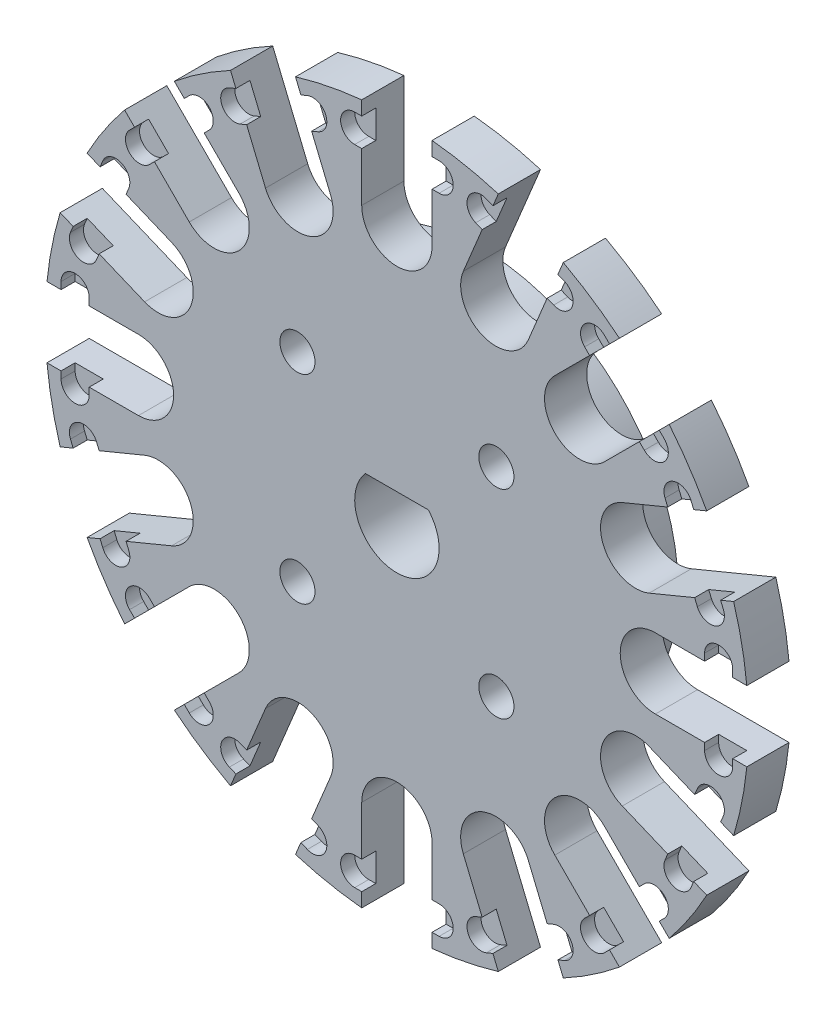
SolidWorks part; units mm, degrees
ref_plane "Plan de face" through (0, 0, 0) normal (0, 0, 1) x (1, 0, 0)
ref_plane "Plan de dessus" through (0, 0, 0) normal (0, 1, 0) x (1, 0, 0)
ref_plane "Plan de droite" through (0, 0, 0) normal (1, 0, 0) x (0, 0, -1)
sketch "Esquisse1" plane through (0, 0, 0) normal (0, 0, 1) x (1, 0, 0)
  circle A0 centre (0, 0) radius 25
  dimension "D1" = 50
extrude "Extrusion1" add sketch "Esquisse1" along normal blind 3
sketch "Esquisse2" plane through (0, 0, 3) normal (0, 0, 1) x (1, 0, 0)
  line L0 (-2.2361, 2) -> (2.2361, 2)
  line L1 (0, 35.6055) -> (0, -30.9749) construction
  line L2 (-2.5, 24.8747) -> (-2.5, 18.3747)
  line L3 (2.5, 24.8747) -> (2.5, 18.3747)
  line L4 (7.2094, 23.9379) -> (4.722, 17.9327)
  line L5 (11.8288, 22.0245) -> (9.3414, 16.0193)
  line L6 (15.8213, 19.3568) -> (11.2251, 14.7606)
  line L7 (19.3568, 15.8213) -> (14.7606, 11.2251)
  line L8 (22.0245, 11.8288) -> (16.0193, 9.3414)
  line L9 (23.9379, 7.2094) -> (17.9327, 4.722)
  line L10 (24.8747, 2.5) -> (18.3747, 2.5)
  line L11 (24.8747, -2.5) -> (18.3747, -2.5)
  line L12 (23.9379, -7.2094) -> (17.9327, -4.722)
  line L13 (22.0245, -11.8288) -> (16.0193, -9.3414)
  line L14 (19.3568, -15.8213) -> (14.7606, -11.2251)
  line L15 (15.8213, -19.3568) -> (11.2251, -14.7606)
  line L16 (11.8288, -22.0245) -> (9.3414, -16.0193)
  line L17 (7.2094, -23.9379) -> (4.722, -17.9327)
  line L18 (2.5, -24.8747) -> (2.5, -18.3747)
  line L19 (-2.5, -24.8747) -> (-2.5, -18.3747)
  line L20 (-7.2094, -23.9379) -> (-4.722, -17.9327)
  line L21 (-11.8288, -22.0245) -> (-9.3414, -16.0193)
  line L22 (-15.8213, -19.3568) -> (-11.2251, -14.7606)
  line L23 (-19.3568, -15.8213) -> (-14.7606, -11.2251)
  line L24 (-22.0245, -11.8288) -> (-16.0193, -9.3414)
  line L25 (-23.9379, -7.2094) -> (-17.9327, -4.722)
  line L26 (-24.8747, -2.5) -> (-18.3747, -2.5)
  line L27 (-24.8747, 2.5) -> (-18.3747, 2.5)
  line L28 (-23.9379, 7.2094) -> (-17.9327, 4.722)
  line L29 (-22.0245, 11.8288) -> (-16.0193, 9.3414)
  line L30 (-19.3568, 15.8213) -> (-14.7606, 11.2251)
  line L31 (-15.8213, 19.3568) -> (-11.2251, 14.7606)
  line L32 (-11.8288, 22.0245) -> (-9.3414, 16.0193)
  line L33 (-7.2094, 23.9379) -> (-4.722, 17.9327)
  arc A0 (-2.2361, 2) -> (2.2361, 2) centre (0, 0) ccw
  circle A1 centre (0, 0) radius 25 construction
  arc A2 (2.5, 18.3747) -> (-2.5, 18.3747) centre (0, 18.3747) cw
  arc A3 (11.8288, 22.0245) -> (7.2094, 23.9379) centre (0, 0) ccw
  arc A4 (9.3414, 16.0193) -> (4.722, 17.9327) centre (7.0317, 16.976) cw
  arc A5 (19.3568, 15.8213) -> (15.8213, 19.3568) centre (0, 0) ccw
  arc A6 (14.7606, 11.2251) -> (11.2251, 14.7606) centre (12.9929, 12.9929) cw
  arc A7 (23.9379, 7.2094) -> (22.0245, 11.8288) centre (0, 0) ccw
  arc A8 (17.9327, 4.722) -> (16.0193, 9.3414) centre (16.976, 7.0317) cw
  arc A9 (24.8747, -2.5) -> (24.8747, 2.5) centre (0, 0) ccw
  arc A10 (18.3747, -2.5) -> (18.3747, 2.5) centre (18.3747, 0) cw
  arc A11 (22.0245, -11.8288) -> (23.9379, -7.2094) centre (0, 0) ccw
  arc A12 (16.0193, -9.3414) -> (17.9327, -4.722) centre (16.976, -7.0317) cw
  arc A13 (15.8213, -19.3568) -> (19.3568, -15.8213) centre (0, 0) ccw
  arc A14 (11.2251, -14.7606) -> (14.7606, -11.2251) centre (12.9929, -12.9929) cw
  arc A15 (7.2094, -23.9379) -> (11.8288, -22.0245) centre (0, 0) ccw
  arc A16 (4.722, -17.9327) -> (9.3414, -16.0193) centre (7.0317, -16.976) cw
  arc A17 (-2.5, -24.8747) -> (2.5, -24.8747) centre (0, 0) ccw
  arc A18 (-2.5, -18.3747) -> (2.5, -18.3747) centre (0, -18.3747) cw
  arc A19 (-11.8288, -22.0245) -> (-7.2094, -23.9379) centre (0, 0) ccw
  arc A20 (-9.3414, -16.0193) -> (-4.722, -17.9327) centre (-7.0317, -16.976) cw
  arc A21 (-19.3568, -15.8213) -> (-15.8213, -19.3568) centre (0, 0) ccw
  arc A22 (-14.7606, -11.2251) -> (-11.2251, -14.7606) centre (-12.9929, -12.9929) cw
  arc A23 (-23.9379, -7.2094) -> (-22.0245, -11.8288) centre (0, 0) ccw
  arc A24 (-17.9327, -4.722) -> (-16.0193, -9.3414) centre (-16.976, -7.0317) cw
  arc A25 (-24.8747, 2.5) -> (-24.8747, -2.5) centre (0, 0) ccw
  arc A26 (-18.3747, 2.5) -> (-18.3747, -2.5) centre (-18.3747, 0) cw
  arc A27 (-22.0245, 11.8288) -> (-23.9379, 7.2094) centre (0, 0) ccw
  arc A28 (-16.0193, 9.3414) -> (-17.9327, 4.722) centre (-16.976, 7.0317) cw
  arc A29 (-15.8213, 19.3568) -> (-19.3568, 15.8213) centre (0, 0) ccw
  arc A30 (-11.2251, 14.7606) -> (-14.7606, 11.2251) centre (-12.9929, 12.9929) cw
  arc A31 (-7.2094, 23.9379) -> (-11.8288, 22.0245) centre (0, 0) ccw
  arc A32 (-4.722, 17.9327) -> (-9.3414, 16.0193) centre (-7.0317, 16.976) cw
  arc A58 (2.5, 24.8747) -> (-2.5, 24.8747) centre (0, 0) ccw
  dimension "D1" = 6
  dimension "D2" = 2
  dimension "D3" = 5
  dimension "D4" = 6.5
extrude "Extrusion3" cut sketch "Esquisse2" against normal blind 10
hole_wizard "Trou taraudé M3x0.51" positions "Esquisse3D2" profile "Esquisse6" tap size "M3x0.5" standard "Ansi Métrique" end condition through all
sketch3d "Esquisse3D2"
  line L0 (-7.0711, 7.0711, 3) -> (-7.0711, -7.0711, 3) construction
  line L1 (-7.0711, -7.0711, 3) -> (7.0711, -7.0711, 3) construction
  circle A4 centre (0, 0, 3) radius 10
  arc A6 (-19.3568, 15.8213, 3) -> (-22.0245, 11.8288, 3) centre (0, 0, 3) ccw construction
  point P0 (-7.0711, 7.0711, 3)
  point P2 (7.0711, 7.0711, 3)
  point P4 (7.0711, -7.0711, 3)
  point P6 (-7.0711, -7.0711, 3)
  point P26 (0, 0, 13)
  point P38 (0, 0, 28)
  dimension "D1" = 20
sketch "Esquisse6" plane through (-7.0711, 7.0711, 3) normal (1, 0, 0) x (0, -1, 0)
  line L0 (0, 0) -> (0, 3)
  line L1 (0, 3) -> (1.25, 3)
  line L2 (1.25, 3) -> (1.25, 0)
  line L5 (1.25, 0) -> (0, 0)
  line L11 (0, -6.35) -> (0, 107.95) construction
  dimension "Diamètre du trou pour taraudage jusqu'au prochain" = 2.5
  dimension "Profondeur du trou pour taraudage jusqu'au prochain" = 3
cosmetic thread "Filetage de perçage1" parameters "D2"=3
cosmetic thread "Filetage de perçage2" parameters "D2"=3
cosmetic thread "Filetage de perçage3" parameters "D2"=3
cosmetic thread "Filetage de perçage4" parameters "D2"=3
sketch "Esquisse9" plane through (0, 0, 0) normal (0, 0, -1) x (-1, 0, 0)
  line L0 (-2.2361, 2) -> (2.2361, 2)
  circle A0 centre (-7.0711, 7.0711) radius 2.75
  circle A1 centre (7.0711, 7.0711) radius 2.75
  circle A2 centre (7.0711, -7.0711) radius 2.75
  circle A3 centre (-7.0711, -7.0711) radius 2.75
  circle A4 centre (0, 0) radius 14
  arc A5 (-2.2361, 2) -> (2.2361, 2) centre (0, 0) ccw
  dimension "D1" = 5.5
  dimension "D2" = 28
extrude "Extrusion6" add sketch "Esquisse9" along normal blind 3
sketch "Esquisse8" plane through (0, 0, 3) normal (0, 0, 1) x (1, 0, 0)
  line L0 (-2.5, 24.8747) -> (-2.5, 18.3747) construction
  line L1 (-2.5, 23.8747) -> (-3, 23.8747)
  line L2 (-2.5, 23.8747) -> (-2.5, 21.8747)
  line L3 (-2.5, 21.8747) -> (-3, 21.8747)
  line L4 (6.8267, 23.014) -> (6.3648, 23.2054)
  line L5 (2.5, 18.3747) -> (2.5, 24.8747) construction
  line L6 (2.5, 23.8747) -> (3, 23.8747)
  line L7 (2.5, 23.8747) -> (2.5, 21.8747)
  line L8 (2.5, 21.8747) -> (3, 21.8747)
  line L9 (6.8267, 23.014) -> (6.0614, 21.1663)
  line L10 (6.0614, 21.1663) -> (5.5994, 21.3576)
  line L11 (11.4461, 21.1006) -> (11.9081, 20.9093)
  line L12 (11.4461, 21.1006) -> (10.6808, 19.2529)
  line L13 (10.6808, 19.2529) -> (11.1427, 19.0615)
  line L14 (15.1142, 18.6497) -> (14.7606, 19.0033)
  line L15 (15.1142, 18.6497) -> (13.7, 17.2355)
  line L16 (13.7, 17.2355) -> (13.3464, 17.5891)
  line L17 (18.6497, 15.1142) -> (19.0033, 14.7606)
  line L18 (18.6497, 15.1142) -> (17.2355, 13.7)
  line L19 (17.2355, 13.7) -> (17.5891, 13.3464)
  line L20 (21.1006, 11.4461) -> (20.9093, 11.9081)
  line L21 (21.1006, 11.4461) -> (19.2529, 10.6808)
  line L22 (19.2529, 10.6808) -> (19.0615, 11.1427)
  line L23 (23.014, 6.8267) -> (23.2054, 6.3648)
  line L24 (23.014, 6.8267) -> (21.1663, 6.0614)
  line L25 (21.1663, 6.0614) -> (21.3576, 5.5994)
  line L26 (23.8747, 2.5) -> (23.8747, 3)
  line L27 (23.8747, 2.5) -> (21.8747, 2.5)
  line L28 (21.8747, 2.5) -> (21.8747, 3)
  line L29 (23.8747, -2.5) -> (23.8747, -3)
  line L30 (23.8747, -2.5) -> (21.8747, -2.5)
  line L31 (21.8747, -2.5) -> (21.8747, -3)
  line L32 (23.014, -6.8267) -> (23.2054, -6.3648)
  line L33 (23.014, -6.8267) -> (21.1663, -6.0614)
  line L34 (21.1663, -6.0614) -> (21.3576, -5.5994)
  line L35 (21.1006, -11.4461) -> (20.9093, -11.9081)
  line L36 (21.1006, -11.4461) -> (19.2529, -10.6808)
  line L37 (19.2529, -10.6808) -> (19.0615, -11.1427)
  line L38 (18.6497, -15.1142) -> (19.0033, -14.7606)
  line L39 (18.6497, -15.1142) -> (17.2355, -13.7)
  line L40 (17.2355, -13.7) -> (17.5891, -13.3464)
  line L41 (15.1142, -18.6497) -> (14.7606, -19.0033)
  line L42 (15.1142, -18.6497) -> (13.7, -17.2355)
  line L43 (13.7, -17.2355) -> (13.3464, -17.5891)
  line L44 (11.4461, -21.1006) -> (11.9081, -20.9093)
  line L45 (11.4461, -21.1006) -> (10.6808, -19.2529)
  line L46 (10.6808, -19.2529) -> (11.1427, -19.0615)
  line L47 (6.8267, -23.014) -> (6.3648, -23.2054)
  line L48 (6.8267, -23.014) -> (6.0614, -21.1663)
  line L49 (6.0614, -21.1663) -> (5.5994, -21.3576)
  line L50 (2.5, -23.8747) -> (3, -23.8747)
  line L51 (2.5, -23.8747) -> (2.5, -21.8747)
  line L52 (2.5, -21.8747) -> (3, -21.8747)
  line L53 (-2.5, -23.8747) -> (-3, -23.8747)
  line L54 (-2.5, -23.8747) -> (-2.5, -21.8747)
  line L55 (-2.5, -21.8747) -> (-3, -21.8747)
  line L56 (-6.8267, -23.014) -> (-6.3648, -23.2054)
  line L57 (-6.8267, -23.014) -> (-6.0614, -21.1663)
  line L58 (-6.0614, -21.1663) -> (-5.5994, -21.3576)
  line L59 (-11.4461, -21.1006) -> (-11.9081, -20.9093)
  line L60 (-11.4461, -21.1006) -> (-10.6808, -19.2529)
  line L61 (-10.6808, -19.2529) -> (-11.1427, -19.0615)
  line L62 (-15.1142, -18.6497) -> (-14.7606, -19.0033)
  line L63 (-15.1142, -18.6497) -> (-13.7, -17.2355)
  line L64 (-13.7, -17.2355) -> (-13.3464, -17.5891)
  line L65 (-18.6497, -15.1142) -> (-19.0033, -14.7606)
  line L66 (-18.6497, -15.1142) -> (-17.2355, -13.7)
  line L67 (-17.2355, -13.7) -> (-17.5891, -13.3464)
  line L68 (-21.1006, -11.4461) -> (-20.9093, -11.9081)
  line L69 (-21.1006, -11.4461) -> (-19.2529, -10.6808)
  line L70 (-19.2529, -10.6808) -> (-19.0615, -11.1427)
  line L71 (-23.014, -6.8267) -> (-23.2054, -6.3648)
  line L72 (-23.014, -6.8267) -> (-21.1663, -6.0614)
  line L73 (-21.1663, -6.0614) -> (-21.3576, -5.5994)
  line L74 (-23.8747, -2.5) -> (-23.8747, -3)
  line L75 (-23.8747, -2.5) -> (-21.8747, -2.5)
  line L76 (-21.8747, -2.5) -> (-21.8747, -3)
  line L77 (-23.8747, 2.5) -> (-23.8747, 3)
  line L78 (-23.8747, 2.5) -> (-21.8747, 2.5)
  line L79 (-21.8747, 2.5) -> (-21.8747, 3)
  line L80 (-23.014, 6.8267) -> (-23.2054, 6.3648)
  line L81 (-23.014, 6.8267) -> (-21.1663, 6.0614)
  line L82 (-21.1663, 6.0614) -> (-21.3576, 5.5994)
  line L83 (-21.1006, 11.4461) -> (-20.9093, 11.9081)
  line L84 (-21.1006, 11.4461) -> (-19.2529, 10.6808)
  line L85 (-19.2529, 10.6808) -> (-19.0615, 11.1427)
  line L86 (-18.6497, 15.1142) -> (-19.0033, 14.7606)
  line L87 (-18.6497, 15.1142) -> (-17.2355, 13.7)
  line L88 (-17.2355, 13.7) -> (-17.5891, 13.3464)
  line L89 (-15.1142, 18.6497) -> (-14.7606, 19.0033)
  line L90 (-15.1142, 18.6497) -> (-13.7, 17.2355)
  line L91 (-13.7, 17.2355) -> (-13.3464, 17.5891)
  line L92 (-11.4461, 21.1006) -> (-11.9081, 20.9093)
  line L93 (-11.4461, 21.1006) -> (-10.6808, 19.2529)
  line L94 (-10.6808, 19.2529) -> (-11.1427, 19.0615)
  line L95 (-6.8267, 23.014) -> (-6.3648, 23.2054)
  line L96 (-6.8267, 23.014) -> (-6.0614, 21.1663)
  line L97 (-6.0614, 21.1663) -> (-5.5994, 21.3576)
  arc A0 (-3, 23.8747) -> (-3, 21.8747) centre (-3, 22.8747) ccw
  arc A1 (3, 21.8747) -> (3, 23.8747) centre (3, 22.8747) ccw
  arc A2 (6.3648, 23.2054) -> (5.5994, 21.3576) centre (5.9821, 22.2815) ccw
  arc A3 (11.1427, 19.0615) -> (11.9081, 20.9093) centre (11.5254, 19.9854) ccw
  arc A4 (14.7606, 19.0033) -> (13.3464, 17.5891) centre (14.0535, 18.2962) ccw
  arc A5 (17.5891, 13.3464) -> (19.0033, 14.7606) centre (18.2962, 14.0535) ccw
  arc A6 (20.9093, 11.9081) -> (19.0615, 11.1427) centre (19.9854, 11.5254) ccw
  arc A7 (21.3576, 5.5994) -> (23.2054, 6.3648) centre (22.2815, 5.9821) ccw
  arc A8 (23.8747, 3) -> (21.8747, 3) centre (22.8747, 3) ccw
  arc A9 (21.8747, -3) -> (23.8747, -3) centre (22.8747, -3) ccw
  arc A10 (23.2054, -6.3648) -> (21.3576, -5.5994) centre (22.2815, -5.9821) ccw
  arc A11 (19.0615, -11.1427) -> (20.9093, -11.9081) centre (19.9854, -11.5254) ccw
  arc A12 (19.0033, -14.7606) -> (17.5891, -13.3464) centre (18.2962, -14.0535) ccw
  arc A13 (13.3464, -17.5891) -> (14.7606, -19.0033) centre (14.0535, -18.2962) ccw
  arc A14 (11.9081, -20.9093) -> (11.1427, -19.0615) centre (11.5254, -19.9854) ccw
  arc A15 (5.5994, -21.3576) -> (6.3648, -23.2054) centre (5.9821, -22.2815) ccw
  arc A16 (3, -23.8747) -> (3, -21.8747) centre (3, -22.8747) ccw
  arc A17 (-3, -21.8747) -> (-3, -23.8747) centre (-3, -22.8747) ccw
  arc A18 (-6.3648, -23.2054) -> (-5.5994, -21.3576) centre (-5.9821, -22.2815) ccw
  arc A19 (-11.1427, -19.0615) -> (-11.9081, -20.9093) centre (-11.5254, -19.9854) ccw
  arc A20 (-14.7606, -19.0033) -> (-13.3464, -17.5891) centre (-14.0535, -18.2962) ccw
  arc A21 (-17.5891, -13.3464) -> (-19.0033, -14.7606) centre (-18.2962, -14.0535) ccw
  arc A22 (-20.9093, -11.9081) -> (-19.0615, -11.1427) centre (-19.9854, -11.5254) ccw
  arc A23 (-21.3576, -5.5994) -> (-23.2054, -6.3648) centre (-22.2815, -5.9821) ccw
  arc A24 (-23.8747, -3) -> (-21.8747, -3) centre (-22.8747, -3) ccw
  arc A25 (-21.8747, 3) -> (-23.8747, 3) centre (-22.8747, 3) ccw
  arc A26 (-23.2054, 6.3648) -> (-21.3576, 5.5994) centre (-22.2815, 5.9821) ccw
  arc A27 (-19.0615, 11.1427) -> (-20.9093, 11.9081) centre (-19.9854, 11.5254) ccw
  arc A28 (-19.0033, 14.7606) -> (-17.5891, 13.3464) centre (-18.2962, 14.0535) ccw
  arc A29 (-13.3464, 17.5891) -> (-14.7606, 19.0033) centre (-14.0535, 18.2962) ccw
  arc A30 (-11.9081, 20.9093) -> (-11.1427, 19.0615) centre (-11.5254, 19.9854) ccw
  arc A31 (-5.5994, 21.3576) -> (-6.3648, 23.2054) centre (-5.9821, 22.2815) ccw
  dimension "D2" = 1
  dimension "D5" = 1
  dimension "D1" = 2
  dimension "D3" = 1
  dimension "D4" = 0.5
  dimension "D6" = 2
  dimension "D7" = 0.5
  dimension "D8" = 1
extrude "Extrusion5" cut sketch "Esquisse8" against normal blind 1
